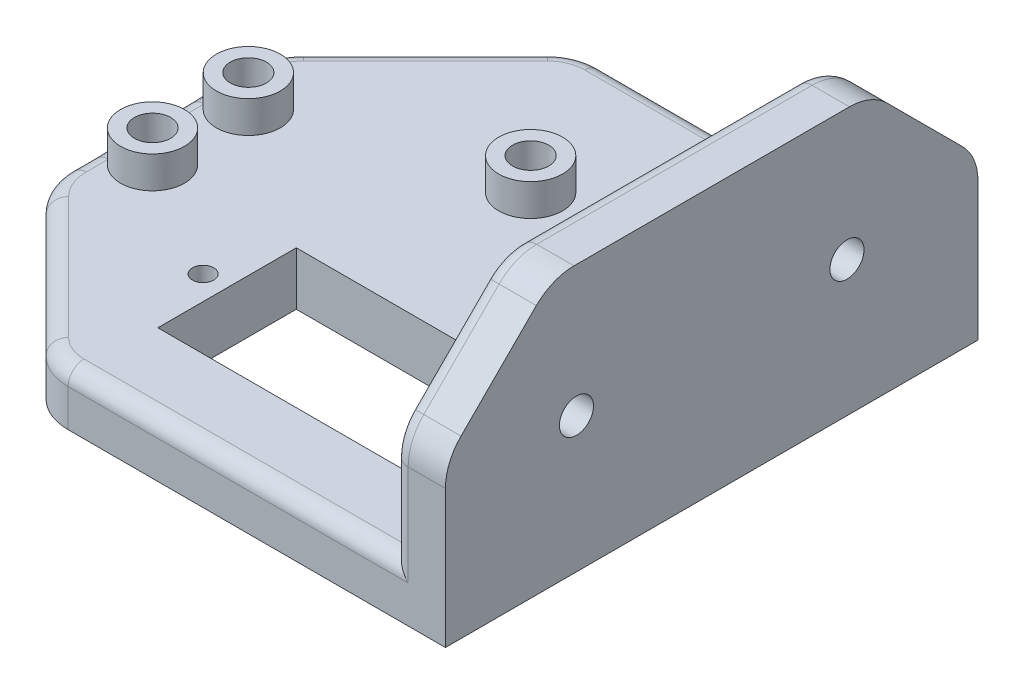
SolidWorks part; units mm, degrees
ref_plane "Front Plane" through (0, 0, 0) normal (0, 0, 1) x (1, 0, 0)
ref_plane "Top Plane" through (0, 0, 0) normal (0, 1, 0) x (1, 0, 0)
ref_plane "Right Plane" through (0, 0, 0) normal (1, 0, 0) x (0, 0, -1)
ref_plane "Plane1" through (57.6167, 0, 0) normal (1, 0, 0) x (0, 0, -1)
sketch "Sketch1" plane through (57.6167, 0, 0) normal (1, 0, 0) x (0, 0, -1)
  line L0 (-6.2383, 15) -> (43.7617, 15)
  line L1 (43.7617, 15) -> (33.7617, 25)
  line L2 (33.7617, 25) -> (3.7617, 25)
  line L3 (3.7617, 25) -> (-6.2383, 15)
extrude "Boss-Extrude1" add sketch "Sketch1" against normal blind 5
sketch "Sketch2" plane through (0, 15, 0) normal (0, -1, 0) x (1, 0, 0)
  line L0 (52.6167, -43.7617) -> (52.6167, 6.2383)
  line L1 (52.6167, 6.2383) -> (57.6167, 6.2383)
  line L2 (57.6167, 6.2383) -> (57.6167, -43.7617)
  line L3 (57.6167, -43.7617) -> (52.6167, -43.7617)
extrude "Boss-Extrude2" add sketch "Sketch2" along normal blind 10
sketch "Sketch3" plane through (0, 5, 0) normal (0, -1, 0) x (1, 0, 0)
  line L0 (5.5889, -29.2339) -> (5.5889, -8.2895)
  line L1 (5.5889, -8.2895) -> (20.1167, 6.2383)
  line L2 (20.1167, 6.2383) -> (57.6167, 6.2383)
  line L3 (57.6167, 6.2383) -> (57.6167, -43.7617)
  line L4 (57.6167, -43.7617) -> (20.1167, -43.7617)
  line L5 (20.1167, -43.7617) -> (5.5889, -29.2339)
extrude "Boss-Extrude3" add sketch "Sketch3" along normal blind 5
sketch "Sketch4" plane through (0, 5, 0) normal (0, 1, 0) x (-1, 0, 0)
  circle A0 centre (-29.6167, -29.7617) radius 3
extrude "Boss-Extrude4" add sketch "Sketch4" along normal blind 3
sketch "Sketch5" plane through (0, 8, 0) normal (0, 1, 0) x (-1, 0, 0)
  circle A0 centre (-29.6167, -29.7617) radius 1.7
extrude "Cut-Extrude1" cut sketch "Sketch5" against normal blind 3
sketch "Sketch6" plane through (0, 0, 0) normal (0, -1, 0) x (1, 0, 0)
  circle A0 centre (29.6167, -29.7617) radius 1.65
extrude "Cut-Extrude2" cut sketch "Sketch6" against normal through all
sketch "Sketch7" plane through (0, 5, 0) normal (0, 1, 0) x (-1, 0, 0)
  circle A0 centre (-9.6167, -23.2617) radius 3
extrude "Boss-Extrude5" add sketch "Sketch7" along normal blind 3
sketch "Sketch8" plane through (0, 8, 0) normal (0, 1, 0) x (-1, 0, 0)
  circle A0 centre (-9.6167, -23.2617) radius 1.7
extrude "Cut-Extrude3" cut sketch "Sketch8" against normal blind 3
sketch "Sketch9" plane through (0, 0, 0) normal (0, -1, 0) x (1, 0, 0)
  circle A0 centre (9.6167, -23.2617) radius 1.65
extrude "Cut-Extrude4" cut sketch "Sketch9" against normal through all
sketch "Sketch10" plane through (0, 0, 0) normal (0, -1, 0) x (1, 0, 0)
  line L0 (23.1167, -1.2617) -> (23.1167, -14.2617)
  line L1 (23.1167, -14.2617) -> (46.1167, -14.2617)
  line L2 (46.1167, -14.2617) -> (46.1167, -1.2617)
  line L3 (46.1167, -1.2617) -> (23.1167, -1.2617)
extrude "Cut-Extrude5" cut sketch "Sketch10" against normal through all
sketch "Sketch11" plane through (0, 5, 0) normal (0, 1, 0) x (-1, 0, 0)
  circle A0 centre (-9.6167, -14.2617) radius 3
extrude "Boss-Extrude6" add sketch "Sketch11" along normal blind 3
sketch "Sketch12" plane through (0, 8, 0) normal (0, 1, 0) x (-1, 0, 0)
  circle A0 centre (-9.6167, -14.2617) radius 1.7
extrude "Cut-Extrude6" cut sketch "Sketch12" against normal blind 3
sketch "Sketch13" plane through (0, 0, 0) normal (0, -1, 0) x (1, 0, 0)
  circle A0 centre (9.6167, -14.2617) radius 1.65
extrude "Cut-Extrude7" cut sketch "Sketch13" against normal through all
hole_wizard "#1 Clearance Hole1" positions "Sketch15" profile "Sketch14" hole size "#1" standard "ANSI Inch"
sketch "Sketch15" plane through (0, 0, 0) normal (0, -1, 0) x (-1, 0, 0)
  point P0 (-48.3667, 7.7617)
  point P1 (-20.8667, 7.7617)
sketch "Sketch14" plane through (48.3667, 0, -7.7617) normal (1, 0, 0) x (0, 0, -1)
  line L0 (0, 0) -> (0, 25)
  line L1 (0, 25) -> (1, 25)
  line L2 (1, 25) -> (1, 0)
  line L5 (1, 0) -> (0, 0)
  line L11 (0, -6.35) -> (0, 107.95) construction
  dimension "Thru Hole Dia." = 2
  dimension "Thru Hole Depth" = 25
hole_wizard "#4 Clearance Hole1" positions "Sketch17" profile "Sketch16" hole size "#4" standard "ANSI Inch" end condition through all
sketch "Sketch17" plane through (57.6167, 0, 0) normal (1, 0, 0) x (0, 0, -1)
  line L0 (31.4617, 12.7) -> (6.0617, 12.7) construction
  line L2 (33.7617, 25) -> (3.7617, 25) construction
  line L3 (43.7617, 0) -> (-6.2383, 0) construction
  point P0 (31.4617, 12.7)
  point P1 (6.0617, 12.7)
  point P9 (18.7617, 25)
  point P10 (18.7617, 12.7)
  point P11 (0, 0)
  dimension "D1" = 25.4
  dimension "D2" = 12.7
sketch "Sketch16" plane through (57.6167, 12.7, -31.4617) normal (0, 1, 0) x (0, 0, -1)
  line L0 (0, 0) -> (0, 52.0278)
  line L1 (0, 52.0278) -> (1.6, 52.0278)
  line L2 (1.6, 52.0278) -> (1.6, 0)
  line L5 (1.6, 0) -> (0, 0)
  line L11 (0, -6.35) -> (0, 107.95) construction
  dimension "Thru Hole Dia." = 3.2
  dimension "Thru Hole Depth" = 52.0278
fillet "Fillet1" radius 5 6 edges at (55.1167, 25, -3.7617) (55.1167, 15, -43.7617) (55.1167, 25, -33.7617) (20.1167, 2.5, -43.7617) (20.1167, 2.5, 6.2383) (55.1167, 15, 6.2383)
fillet "Fillet2" radius 5.5 2 edges at (5.5889, 2.5, -8.2895) (5.5889, 2.5, -29.2339)
fillet "Fillet3" radius 1.5 18 edges at (37.4022, 5, -43.7617) (20.2744, 5, -43.3811) (37.4022, 5, 6.2383) (12.926, 5, -36.571) (20.2744, 5, 5.8577) (6.0076, 5, -29.0605) (12.926, 5, -0.9524) (5.5889, 5, -18.7617) (6.0076, 5, -8.4629) (52.6167, 8.9645, -43.7617) (52.6167, 14.8423, -43.3811) (52.6167, 20, -38.7617) (52.6167, 24.6194, -33.6041) (52.6167, 8.9645, 6.2383) (52.6167, 25, -18.7617) (52.6167, 14.8423, 5.8577) (52.6167, 24.6194, -3.9194) (52.6167, 20, 1.2383)
